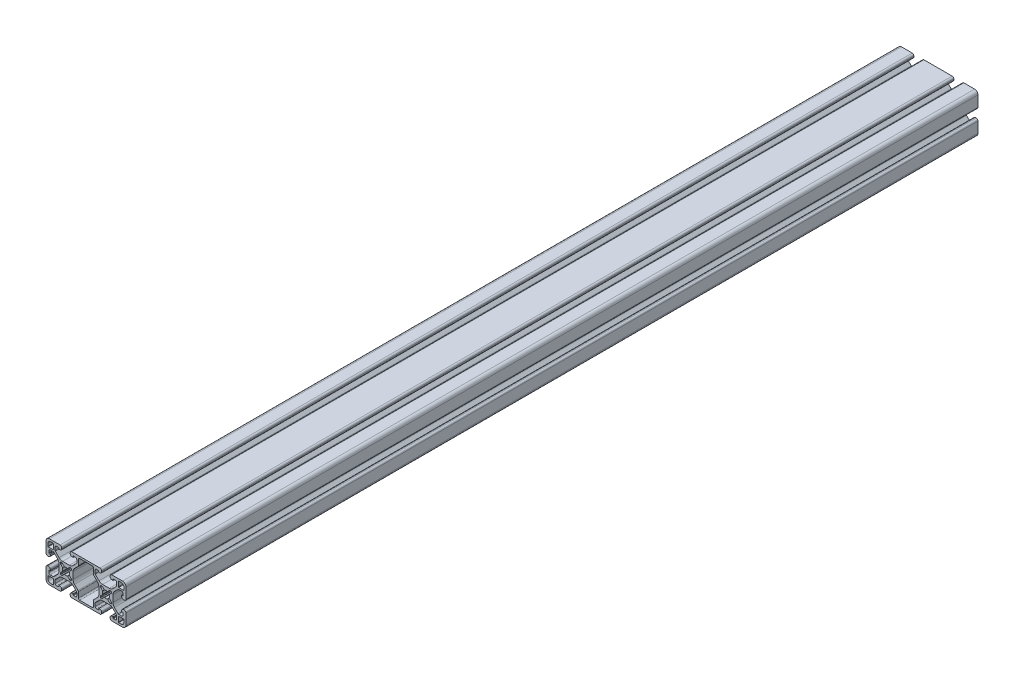
SolidWorks part; units mm, degrees
material "6105-T5 Aluminum"
ref_plane "Front Plane" through (0, 0, 0) normal (0, 0, 1) x (1, 0, 0)
ref_plane "Top Plane" through (0, 0, 0) normal (0, 1, 0) x (1, 0, 0)
ref_plane "Right Plane" through (0, 0, 0) normal (1, 0, 0) x (0, 0, -1)
sketch "Sketch1" plane through (0, 0, 0) normal (0, 0, 1) x (1, 0, 0)
  line L0 (-20.6323, -3.1988) -> (-22.3548, -4.9212)
  line L1 (-22.9834, -5.1816) -> (-23.9776, -5.1816)
  line L2 (-24.2316, -4.9276) -> (-24.2316, -3.9334)
  line L3 (-23.9712, -3.3048) -> (-22.2488, -1.5823)
  line L4 (-22.2488, 1.5823) -> (-23.9712, 3.3048)
  line L5 (-24.2316, 3.9334) -> (-24.2316, 4.9276)
  line L6 (-23.9776, 5.1816) -> (-22.9834, 5.1816)
  line L7 (-22.3548, 4.9212) -> (-20.6323, 3.1988)
  line L8 (-17.4677, 3.1988) -> (-15.7452, 4.9212)
  line L9 (-15.1166, 5.1816) -> (-14.1224, 5.1816)
  line L10 (-13.8684, 4.9276) -> (-13.8684, 3.9334)
  line L11 (-14.1288, 3.3048) -> (-15.8512, 1.5823)
  line L12 (-15.8512, -1.5823) -> (-14.1288, -3.3048)
  line L13 (-13.8684, -3.9334) -> (-13.8684, -4.9276)
  line L14 (-14.1224, -5.1816) -> (-15.1166, -5.1816)
  line L15 (-15.7452, -4.9212) -> (-17.4677, -3.1988)
  line L16 (30.9118, -16.8656) -> (30.9118, -12.2428)
  line L17 (31.2928, -11.8618) -> (35.9156, -11.8618)
  line L18 (36.2966, -12.2428) -> (36.2966, -14.4526)
  line L19 (33.5026, -17.2466) -> (31.2928, -17.2466)
  line L20 (35.9156, 11.8618) -> (31.2928, 11.8618)
  line L21 (30.9118, 12.2428) -> (30.9118, 16.8656)
  line L22 (31.2928, 17.2466) -> (33.5026, 17.2466)
  line L23 (36.2966, 14.4526) -> (36.2966, 12.2428)
  line L24 (5.9182, -17.2466) -> (-5.9182, -17.2466)
  line L25 (-7.1882, -15.9766) -> (-7.1882, -10.8253)
  line L26 (-7.5602, -9.9273) -> (-10.9208, -6.5666)
  line L27 (-12.312, -3.208) -> (-12.312, 3.208)
  line L28 (-10.9208, 6.5666) -> (-7.5602, 9.9273)
  line L29 (-7.1882, 10.8253) -> (-7.1882, 15.9766)
  line L30 (-5.9182, 17.2466) -> (5.9182, 17.2466)
  line L31 (7.1882, 15.9766) -> (7.1882, 10.8253)
  line L32 (7.5602, 9.9273) -> (10.9208, 6.5666)
  line L33 (12.312, 3.208) -> (12.312, -3.208)
  line L34 (10.9208, -6.5666) -> (7.5602, -9.9273)
  line L35 (7.1882, -10.8253) -> (7.1882, -15.9766)
  line L36 (17.4677, -3.1988) -> (15.7452, -4.9212)
  line L37 (15.1166, -5.1816) -> (14.1224, -5.1816)
  line L38 (13.8684, -4.9276) -> (13.8684, -3.9334)
  line L39 (14.1288, -3.3048) -> (15.8512, -1.5823)
  line L40 (15.8512, 1.5823) -> (14.1288, 3.3048)
  line L41 (13.8684, 3.9334) -> (13.8684, 4.9276)
  line L42 (14.1224, 5.1816) -> (15.1166, 5.1816)
  line L43 (15.7452, 4.9212) -> (17.4677, 3.1988)
  line L44 (20.6323, 3.1988) -> (22.3548, 4.9212)
  line L45 (22.9834, 5.1816) -> (23.9776, 5.1816)
  line L46 (24.2316, 4.9276) -> (24.2316, 3.9334)
  line L47 (23.9712, 3.3048) -> (22.2488, 1.5823)
  line L48 (22.2488, -1.5823) -> (23.9712, -3.3048)
  line L49 (24.2316, -3.9334) -> (24.2316, -4.9276)
  line L50 (23.9776, -5.1816) -> (22.9834, -5.1816)
  line L51 (22.3548, -4.9212) -> (20.6323, -3.1988)
  line L52 (-35.9156, -11.8618) -> (-31.2928, -11.8618)
  line L53 (-30.9118, -12.2428) -> (-30.9118, -16.8656)
  line L54 (-31.2928, -17.2466) -> (-33.5026, -17.2466)
  line L55 (-36.2966, -14.4526) -> (-36.2966, -12.2428)
  line L56 (-30.9118, 16.8656) -> (-30.9118, 12.2428)
  line L57 (-31.2928, 11.8618) -> (-35.9156, 11.8618)
  line L58 (-36.2966, 12.2428) -> (-36.2966, 14.4526)
  line L59 (-33.5026, 17.2466) -> (-31.2928, 17.2466)
  line L60 (35.3359, -7.239) -> (35.3359, -9.017)
  line L61 (34.0659, -10.287) -> (31.2678, -10.287)
  line L62 (30.6392, -10.0266) -> (27.1792, -6.5666)
  line L63 (25.788, -3.208) -> (25.788, 3.208)
  line L64 (27.1792, 6.5666) -> (30.6392, 10.0266)
  line L65 (31.2678, 10.287) -> (34.0659, 10.287)
  line L66 (35.3359, 9.017) -> (35.3359, 7.239)
  line L67 (34.9549, 6.858) -> (34.036, 6.858)
  line L68 (34.036, 6.858) -> (34.036, 5.6388)
  line L69 (35.6108, 4.064) -> (36.5252, 4.064)
  line L70 (38.1, 5.6388) -> (38.1, 15.875)
  line L71 (34.925, 19.05) -> (24.6888, 19.05)
  line L72 (23.114, 17.4752) -> (23.114, 16.5608)
  line L73 (24.6888, 14.986) -> (25.908, 14.986)
  line L74 (25.908, 14.986) -> (25.908, 15.9049)
  line L75 (26.289, 16.2859) -> (28.067, 16.2859)
  line L76 (29.337, 15.0159) -> (29.337, 12.2178)
  line L77 (29.0766, 11.5892) -> (25.6166, 8.1292)
  line L78 (22.258, 6.738) -> (15.842, 6.738)
  line L79 (12.4834, 8.1292) -> (9.0234, 11.5892)
  line L80 (8.763, 12.2178) -> (8.763, 15.0159)
  line L81 (10.033, 16.2859) -> (11.811, 16.2859)
  line L82 (12.192, 15.9049) -> (12.192, 14.986)
  line L83 (12.192, 14.986) -> (13.4112, 14.986)
  line L84 (14.986, 16.5608) -> (14.986, 17.4752)
  line L85 (13.4112, 19.05) -> (-13.4112, 19.05)
  line L86 (-14.986, 17.4752) -> (-14.986, 16.5608)
  line L87 (-13.4112, 14.986) -> (-12.192, 14.986)
  line L88 (-12.192, 14.986) -> (-12.192, 15.9049)
  line L89 (-11.811, 16.2859) -> (-10.033, 16.2859)
  line L90 (-8.763, 15.0159) -> (-8.763, 12.2178)
  line L91 (-9.0234, 11.5892) -> (-12.4834, 8.1292)
  line L92 (-15.842, 6.738) -> (-22.258, 6.738)
  line L93 (-25.6166, 8.1292) -> (-29.0766, 11.5892)
  line L94 (-29.337, 12.2178) -> (-29.337, 15.0159)
  line L95 (-28.067, 16.2859) -> (-26.289, 16.2859)
  line L96 (-25.908, 15.9049) -> (-25.908, 14.986)
  line L97 (-25.908, 14.986) -> (-24.6888, 14.986)
  line L98 (-23.114, 16.5608) -> (-23.114, 17.4752)
  line L99 (-24.6888, 19.05) -> (-34.925, 19.05)
  line L100 (-38.1, 15.875) -> (-38.1, 5.6388)
  line L101 (-36.5252, 4.064) -> (-35.6108, 4.064)
  line L102 (-34.036, 5.6388) -> (-34.036, 6.858)
  line L103 (-34.036, 6.858) -> (-34.9549, 6.858)
  line L104 (-35.3359, 7.239) -> (-35.3359, 9.017)
  line L105 (-34.0659, 10.287) -> (-31.2678, 10.287)
  line L106 (-30.6392, 10.0266) -> (-27.1792, 6.5666)
  line L107 (-25.788, 3.208) -> (-25.788, -3.208)
  line L108 (-27.1792, -6.5666) -> (-30.6392, -10.0266)
  line L109 (-31.2678, -10.287) -> (-34.0659, -10.287)
  line L110 (-35.3359, -9.017) -> (-35.3359, -7.239)
  line L111 (-34.9549, -6.858) -> (-34.036, -6.858)
  line L112 (-34.036, -6.858) -> (-34.036, -5.6388)
  line L113 (-35.6108, -4.064) -> (-36.5252, -4.064)
  line L114 (-38.1, -5.6388) -> (-38.1, -15.875)
  line L115 (-34.925, -19.05) -> (-24.6888, -19.05)
  line L116 (-23.114, -17.4752) -> (-23.114, -16.5608)
  line L117 (-24.6888, -14.986) -> (-25.908, -14.986)
  line L118 (-25.908, -14.986) -> (-25.908, -15.9049)
  line L119 (-26.289, -16.2859) -> (-28.067, -16.2859)
  line L120 (-29.337, -15.0159) -> (-29.337, -12.2178)
  line L121 (-29.0766, -11.5892) -> (-25.6166, -8.1292)
  line L122 (-22.258, -6.738) -> (-15.842, -6.738)
  line L123 (-12.4834, -8.1292) -> (-9.0234, -11.5892)
  line L124 (-8.763, -12.2178) -> (-8.763, -15.0159)
  line L125 (-10.033, -16.2859) -> (-11.811, -16.2859)
  line L126 (-12.192, -15.9049) -> (-12.192, -14.986)
  line L127 (-12.192, -14.986) -> (-13.4112, -14.986)
  line L128 (-14.986, -16.5608) -> (-14.986, -17.4752)
  line L129 (-13.4112, -19.05) -> (13.4112, -19.05)
  line L130 (14.986, -17.4752) -> (14.986, -16.5608)
  line L131 (13.4112, -14.986) -> (12.192, -14.986)
  line L132 (12.192, -14.986) -> (12.192, -15.9049)
  line L133 (11.811, -16.2859) -> (10.033, -16.2859)
  line L134 (8.763, -15.0159) -> (8.763, -12.2178)
  line L135 (9.0234, -11.5892) -> (12.4834, -8.1292)
  line L136 (15.842, -6.738) -> (22.258, -6.738)
  line L137 (25.6166, -8.1292) -> (29.0766, -11.5892)
  line L138 (29.337, -12.2178) -> (29.337, -15.0159)
  line L139 (28.067, -16.2859) -> (26.289, -16.2859)
  line L140 (25.908, -15.9049) -> (25.908, -14.986)
  line L141 (25.908, -14.986) -> (24.6888, -14.986)
  line L142 (23.114, -16.5608) -> (23.114, -17.4752)
  line L143 (24.6888, -19.05) -> (34.925, -19.05)
  line L144 (38.1, -15.875) -> (38.1, -5.6388)
  line L145 (36.5252, -4.064) -> (35.6108, -4.064)
  line L146 (34.036, -5.6388) -> (34.036, -6.858)
  line L147 (34.036, -6.858) -> (34.9549, -6.858)
  arc A0 (-20.228, -3.1119) -> (-17.872, -3.1119) centre (-19.05, 0) ccw
  arc A1 (-20.228, -3.1119) -> (-20.6323, -3.1988) centre (-20.3629, -3.4682) ccw
  arc A2 (-22.9834, -5.1816) -> (-22.3548, -4.9212) centre (-22.9834, -4.2926) ccw
  arc A3 (-24.2316, -4.9276) -> (-23.9776, -5.1816) centre (-23.9776, -4.9276) ccw
  arc A4 (-23.9712, -3.3048) -> (-24.2316, -3.9334) centre (-23.3426, -3.9334) ccw
  arc A5 (-22.2488, -1.5823) -> (-22.1619, -1.178) centre (-22.5182, -1.3129) ccw
  arc A6 (-22.1619, 1.178) -> (-22.1619, -1.178) centre (-19.05, 0) ccw
  arc A7 (-22.1619, 1.178) -> (-22.2488, 1.5823) centre (-22.5182, 1.3129) ccw
  arc A8 (-24.2316, 3.9334) -> (-23.9712, 3.3048) centre (-23.3426, 3.9334) ccw
  arc A9 (-23.9776, 5.1816) -> (-24.2316, 4.9276) centre (-23.9776, 4.9276) ccw
  arc A10 (-22.3548, 4.9212) -> (-22.9834, 5.1816) centre (-22.9834, 4.2926) ccw
  arc A11 (-20.6323, 3.1988) -> (-20.228, 3.1119) centre (-20.3629, 3.4682) ccw
  arc A12 (-17.872, 3.1119) -> (-20.228, 3.1119) centre (-19.05, 0) ccw
  arc A13 (-17.872, 3.1119) -> (-17.4677, 3.1988) centre (-17.7371, 3.4682) ccw
  arc A14 (-15.1166, 5.1816) -> (-15.7452, 4.9212) centre (-15.1166, 4.2926) ccw
  arc A15 (-13.8684, 4.9276) -> (-14.1224, 5.1816) centre (-14.1224, 4.9276) ccw
  arc A16 (-14.1288, 3.3048) -> (-13.8684, 3.9334) centre (-14.7574, 3.9334) ccw
  arc A17 (-15.8512, 1.5823) -> (-15.9381, 1.178) centre (-15.5818, 1.3129) ccw
  arc A18 (-15.9381, -1.178) -> (-15.9381, 1.178) centre (-19.05, 0) ccw
  arc A19 (-15.9381, -1.178) -> (-15.8512, -1.5823) centre (-15.5818, -1.3129) ccw
  arc A20 (-13.8684, -3.9334) -> (-14.1288, -3.3048) centre (-14.7574, -3.9334) ccw
  arc A21 (-14.1224, -5.1816) -> (-13.8684, -4.9276) centre (-14.1224, -4.9276) ccw
  arc A22 (-15.7452, -4.9212) -> (-15.1166, -5.1816) centre (-15.1166, -4.2926) ccw
  arc A23 (-17.4677, -3.1988) -> (-17.872, -3.1119) centre (-17.7371, -3.4682) ccw
  arc A24 (31.2928, -11.8618) -> (30.9118, -12.2428) centre (31.2928, -12.2428) ccw
  arc A25 (36.2966, -12.2428) -> (35.9156, -11.8618) centre (35.9156, -12.2428) ccw
  arc A26 (33.5026, -17.2466) -> (36.2966, -14.4526) centre (33.5026, -14.4526) ccw
  arc A27 (30.9118, -16.8656) -> (31.2928, -17.2466) centre (31.2928, -16.8656) ccw
  arc A28 (30.9118, 12.2428) -> (31.2928, 11.8618) centre (31.2928, 12.2428) ccw
  arc A29 (31.2928, 17.2466) -> (30.9118, 16.8656) centre (31.2928, 16.8656) ccw
  arc A30 (36.2966, 14.4526) -> (33.5026, 17.2466) centre (33.5026, 14.4526) ccw
  arc A31 (35.9156, 11.8618) -> (36.2966, 12.2428) centre (35.9156, 12.2428) ccw
  arc A32 (5.9182, -17.2466) -> (7.1882, -15.9766) centre (5.9182, -15.9766) ccw
  arc A33 (-7.1882, -15.9766) -> (-5.9182, -17.2466) centre (-5.9182, -15.9766) ccw
  arc A34 (-7.1882, -10.8253) -> (-7.5602, -9.9273) centre (-8.4582, -10.8253) ccw
  arc A35 (-12.312, -3.208) -> (-10.9208, -6.5666) centre (-7.5622, -3.208) ccw
  arc A36 (-10.9208, 6.5666) -> (-12.312, 3.208) centre (-7.5622, 3.208) ccw
  arc A37 (-7.5602, 9.9273) -> (-7.1882, 10.8253) centre (-8.4582, 10.8253) ccw
  arc A38 (-5.9182, 17.2466) -> (-7.1882, 15.9766) centre (-5.9182, 15.9766) ccw
  arc A39 (7.1882, 15.9766) -> (5.9182, 17.2466) centre (5.9182, 15.9766) ccw
  arc A40 (7.1882, 10.8253) -> (7.5602, 9.9273) centre (8.4582, 10.8253) ccw
  arc A41 (12.312, 3.208) -> (10.9208, 6.5666) centre (7.5622, 3.208) ccw
  arc A42 (10.9208, -6.5666) -> (12.312, -3.208) centre (7.5622, -3.208) ccw
  arc A43 (7.5602, -9.9273) -> (7.1882, -10.8253) centre (8.4582, -10.8253) ccw
  arc A44 (17.872, -3.1119) -> (20.228, -3.1119) centre (19.05, 0) ccw
  arc A45 (17.872, -3.1119) -> (17.4677, -3.1988) centre (17.7371, -3.4682) ccw
  arc A46 (15.1166, -5.1816) -> (15.7452, -4.9212) centre (15.1166, -4.2926) ccw
  arc A47 (13.8684, -4.9276) -> (14.1224, -5.1816) centre (14.1224, -4.9276) ccw
  arc A48 (14.1288, -3.3048) -> (13.8684, -3.9334) centre (14.7574, -3.9334) ccw
  arc A49 (15.8512, -1.5823) -> (15.9381, -1.178) centre (15.5818, -1.3129) ccw
  arc A50 (15.9381, 1.178) -> (15.9381, -1.178) centre (19.05, 0) ccw
  arc A51 (15.9381, 1.178) -> (15.8512, 1.5823) centre (15.5818, 1.3129) ccw
  arc A52 (13.8684, 3.9334) -> (14.1288, 3.3048) centre (14.7574, 3.9334) ccw
  arc A53 (14.1224, 5.1816) -> (13.8684, 4.9276) centre (14.1224, 4.9276) ccw
  arc A54 (15.7452, 4.9212) -> (15.1166, 5.1816) centre (15.1166, 4.2926) ccw
  arc A55 (17.4677, 3.1988) -> (17.872, 3.1119) centre (17.7371, 3.4682) ccw
  arc A56 (20.228, 3.1119) -> (17.872, 3.1119) centre (19.05, 0) ccw
  arc A57 (20.228, 3.1119) -> (20.6323, 3.1988) centre (20.3629, 3.4682) ccw
  arc A58 (22.9834, 5.1816) -> (22.3548, 4.9212) centre (22.9834, 4.2926) ccw
  arc A59 (24.2316, 4.9276) -> (23.9776, 5.1816) centre (23.9776, 4.9276) ccw
  arc A60 (23.9712, 3.3048) -> (24.2316, 3.9334) centre (23.3426, 3.9334) ccw
  arc A61 (22.2488, 1.5823) -> (22.1619, 1.178) centre (22.5182, 1.3129) ccw
  arc A62 (22.1619, -1.178) -> (22.1619, 1.178) centre (19.05, 0) ccw
  arc A63 (22.1619, -1.178) -> (22.2488, -1.5823) centre (22.5182, -1.3129) ccw
  arc A64 (24.2316, -3.9334) -> (23.9712, -3.3048) centre (23.3426, -3.9334) ccw
  arc A65 (23.9776, -5.1816) -> (24.2316, -4.9276) centre (23.9776, -4.9276) ccw
  arc A66 (22.3548, -4.9212) -> (22.9834, -5.1816) centre (22.9834, -4.2926) ccw
  arc A67 (20.6323, -3.1988) -> (20.228, -3.1119) centre (20.3629, -3.4682) ccw
  arc A68 (-30.9118, -12.2428) -> (-31.2928, -11.8618) centre (-31.2928, -12.2428) ccw
  arc A69 (-31.2928, -17.2466) -> (-30.9118, -16.8656) centre (-31.2928, -16.8656) ccw
  arc A70 (-36.2966, -14.4526) -> (-33.5026, -17.2466) centre (-33.5026, -14.4526) ccw
  arc A71 (-35.9156, -11.8618) -> (-36.2966, -12.2428) centre (-35.9156, -12.2428) ccw
  arc A72 (-31.2928, 11.8618) -> (-30.9118, 12.2428) centre (-31.2928, 12.2428) ccw
  arc A73 (-36.2966, 12.2428) -> (-35.9156, 11.8618) centre (-35.9156, 12.2428) ccw
  arc A74 (-33.5026, 17.2466) -> (-36.2966, 14.4526) centre (-33.5026, 14.4526) ccw
  arc A75 (-30.9118, 16.8656) -> (-31.2928, 17.2466) centre (-31.2928, 16.8656) ccw
  arc A76 (35.3359, -7.239) -> (34.9549, -6.858) centre (34.9549, -7.239) ccw
  arc A77 (34.0659, -10.287) -> (35.3359, -9.017) centre (34.0659, -9.017) ccw
  arc A78 (30.6392, -10.0266) -> (31.2678, -10.287) centre (31.2678, -9.398) ccw
  arc A79 (25.788, -3.208) -> (27.1792, -6.5666) centre (30.5378, -3.208) ccw
  arc A80 (27.1792, 6.5666) -> (25.788, 3.208) centre (30.5378, 3.208) ccw
  arc A81 (31.2678, 10.287) -> (30.6392, 10.0266) centre (31.2678, 9.398) ccw
  arc A82 (35.3359, 9.017) -> (34.0659, 10.287) centre (34.0659, 9.017) ccw
  arc A83 (34.9549, 6.858) -> (35.3359, 7.239) centre (34.9549, 7.239) ccw
  arc A84 (34.036, 5.6388) -> (35.6108, 4.064) centre (35.6108, 5.6388) ccw
  arc A85 (36.5252, 4.064) -> (38.1, 5.6388) centre (36.5252, 5.6388) ccw
  arc A86 (38.1, 15.875) -> (34.925, 19.05) centre (34.925, 15.875) ccw
  arc A87 (24.6888, 19.05) -> (23.114, 17.4752) centre (24.6888, 17.4752) ccw
  arc A88 (23.114, 16.5608) -> (24.6888, 14.986) centre (24.6888, 16.5608) ccw
  arc A89 (26.289, 16.2859) -> (25.908, 15.9049) centre (26.289, 15.9049) ccw
  arc A90 (29.337, 15.0159) -> (28.067, 16.2859) centre (28.067, 15.0159) ccw
  arc A91 (29.0766, 11.5892) -> (29.337, 12.2178) centre (28.448, 12.2178) ccw
  arc A92 (22.258, 6.738) -> (25.6166, 8.1292) centre (22.258, 11.4878) ccw
  arc A93 (12.4834, 8.1292) -> (15.842, 6.738) centre (15.842, 11.4878) ccw
  arc A94 (8.763, 12.2178) -> (9.0234, 11.5892) centre (9.652, 12.2178) ccw
  arc A95 (10.033, 16.2859) -> (8.763, 15.0159) centre (10.033, 15.0159) ccw
  arc A96 (12.192, 15.9049) -> (11.811, 16.2859) centre (11.811, 15.9049) ccw
  arc A97 (13.4112, 14.986) -> (14.986, 16.5608) centre (13.4112, 16.5608) ccw
  arc A98 (14.986, 17.4752) -> (13.4112, 19.05) centre (13.4112, 17.4752) ccw
  arc A99 (-13.4112, 19.05) -> (-14.986, 17.4752) centre (-13.4112, 17.4752) ccw
  arc A100 (-14.986, 16.5608) -> (-13.4112, 14.986) centre (-13.4112, 16.5608) ccw
  arc A101 (-11.811, 16.2859) -> (-12.192, 15.9049) centre (-11.811, 15.9049) ccw
  arc A102 (-8.763, 15.0159) -> (-10.033, 16.2859) centre (-10.033, 15.0159) ccw
  arc A103 (-9.0234, 11.5892) -> (-8.763, 12.2178) centre (-9.652, 12.2178) ccw
  arc A104 (-15.842, 6.738) -> (-12.4834, 8.1292) centre (-15.842, 11.4878) ccw
  arc A105 (-25.6166, 8.1292) -> (-22.258, 6.738) centre (-22.258, 11.4878) ccw
  arc A106 (-29.337, 12.2178) -> (-29.0766, 11.5892) centre (-28.448, 12.2178) ccw
  arc A107 (-28.067, 16.2859) -> (-29.337, 15.0159) centre (-28.067, 15.0159) ccw
  arc A108 (-25.908, 15.9049) -> (-26.289, 16.2859) centre (-26.289, 15.9049) ccw
  arc A109 (-24.6888, 14.986) -> (-23.114, 16.5608) centre (-24.6888, 16.5608) ccw
  arc A110 (-23.114, 17.4752) -> (-24.6888, 19.05) centre (-24.6888, 17.4752) ccw
  arc A111 (-34.925, 19.05) -> (-38.1, 15.875) centre (-34.925, 15.875) ccw
  arc A112 (-38.1, 5.6388) -> (-36.5252, 4.064) centre (-36.5252, 5.6388) ccw
  arc A113 (-35.6108, 4.064) -> (-34.036, 5.6388) centre (-35.6108, 5.6388) ccw
  arc A114 (-35.3359, 7.239) -> (-34.9549, 6.858) centre (-34.9549, 7.239) ccw
  arc A115 (-34.0659, 10.287) -> (-35.3359, 9.017) centre (-34.0659, 9.017) ccw
  arc A116 (-30.6392, 10.0266) -> (-31.2678, 10.287) centre (-31.2678, 9.398) ccw
  arc A117 (-25.788, 3.208) -> (-27.1792, 6.5666) centre (-30.5378, 3.208) ccw
  arc A118 (-27.1792, -6.5666) -> (-25.788, -3.208) centre (-30.5378, -3.208) ccw
  arc A119 (-31.2678, -10.287) -> (-30.6392, -10.0266) centre (-31.2678, -9.398) ccw
  arc A120 (-35.3359, -9.017) -> (-34.0659, -10.287) centre (-34.0659, -9.017) ccw
  arc A121 (-34.9549, -6.858) -> (-35.3359, -7.239) centre (-34.9549, -7.239) ccw
  arc A122 (-34.036, -5.6388) -> (-35.6108, -4.064) centre (-35.6108, -5.6388) ccw
  arc A123 (-36.5252, -4.064) -> (-38.1, -5.6388) centre (-36.5252, -5.6388) ccw
  arc A124 (-38.1, -15.875) -> (-34.925, -19.05) centre (-34.925, -15.875) ccw
  arc A125 (-24.6888, -19.05) -> (-23.114, -17.4752) centre (-24.6888, -17.4752) ccw
  arc A126 (-23.114, -16.5608) -> (-24.6888, -14.986) centre (-24.6888, -16.5608) ccw
  arc A127 (-26.289, -16.2859) -> (-25.908, -15.9049) centre (-26.289, -15.9049) ccw
  arc A128 (-29.337, -15.0159) -> (-28.067, -16.2859) centre (-28.067, -15.0159) ccw
  arc A129 (-29.0766, -11.5892) -> (-29.337, -12.2178) centre (-28.448, -12.2178) ccw
  arc A130 (-22.258, -6.738) -> (-25.6166, -8.1292) centre (-22.258, -11.4878) ccw
  arc A131 (-12.4834, -8.1292) -> (-15.842, -6.738) centre (-15.842, -11.4878) ccw
  arc A132 (-8.763, -12.2178) -> (-9.0234, -11.5892) centre (-9.652, -12.2178) ccw
  arc A133 (-10.033, -16.2859) -> (-8.763, -15.0159) centre (-10.033, -15.0159) ccw
  arc A134 (-12.192, -15.9049) -> (-11.811, -16.2859) centre (-11.811, -15.9049) ccw
  arc A135 (-13.4112, -14.986) -> (-14.986, -16.5608) centre (-13.4112, -16.5608) ccw
  arc A136 (-14.986, -17.4752) -> (-13.4112, -19.05) centre (-13.4112, -17.4752) ccw
  arc A137 (13.4112, -19.05) -> (14.986, -17.4752) centre (13.4112, -17.4752) ccw
  arc A138 (14.986, -16.5608) -> (13.4112, -14.986) centre (13.4112, -16.5608) ccw
  arc A139 (11.811, -16.2859) -> (12.192, -15.9049) centre (11.811, -15.9049) ccw
  arc A140 (8.763, -15.0159) -> (10.033, -16.2859) centre (10.033, -15.0159) ccw
  arc A141 (9.0234, -11.5892) -> (8.763, -12.2178) centre (9.652, -12.2178) ccw
  arc A142 (15.842, -6.738) -> (12.4834, -8.1292) centre (15.842, -11.4878) ccw
  arc A143 (25.6166, -8.1292) -> (22.258, -6.738) centre (22.258, -11.4878) ccw
  arc A144 (29.337, -12.2178) -> (29.0766, -11.5892) centre (28.448, -12.2178) ccw
  arc A145 (28.067, -16.2859) -> (29.337, -15.0159) centre (28.067, -15.0159) ccw
  arc A146 (25.908, -15.9049) -> (26.289, -16.2859) centre (26.289, -15.9049) ccw
  arc A147 (24.6888, -14.986) -> (23.114, -16.5608) centre (24.6888, -16.5608) ccw
  arc A148 (23.114, -17.4752) -> (24.6888, -19.05) centre (24.6888, -17.4752) ccw
  arc A149 (34.925, -19.05) -> (38.1, -15.875) centre (34.925, -15.875) ccw
  arc A150 (38.1, -5.6388) -> (36.5252, -4.064) centre (36.5252, -5.6388) ccw
  arc A151 (35.6108, -4.064) -> (34.036, -5.6388) centre (35.6108, -5.6388) ccw
extrude "Extrude1" add sketch "Sketch1" against normal blind 812.8
sketch "Sketch2" plane through (0, 19.05, 0) normal (0, 1, 0) x (1, 0, 0)
  line L0 (-38.1, 812.8) -> (-38.1, 0) construction
  line L1 (13.4112, 812.8) -> (-13.4112, 812.8) construction
  circle A0 centre (-19.05, 577.85) radius 3.7567
  dimension "D3" = 7.5133
  dimension "D1" = 19.05
  dimension "D2" = 234.95
extrude "Cut-Extrude1" cut sketch "Sketch2" against normal through all
